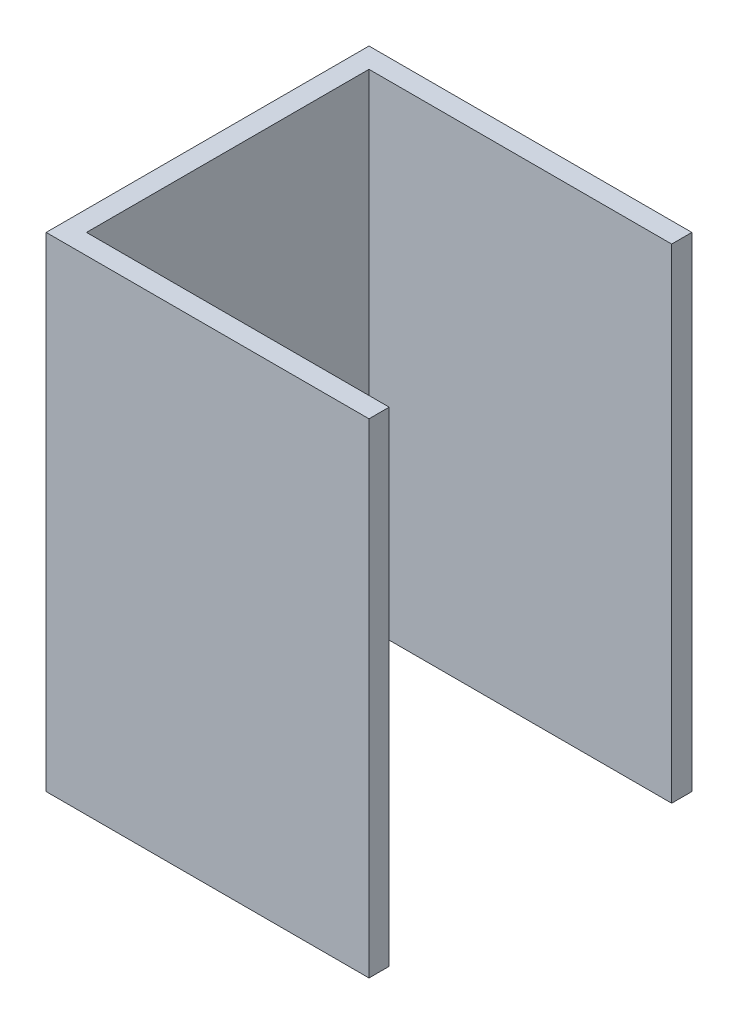
SolidWorks part; units mm, degrees
ref_plane "Front Plane" through (0, 0, 0) normal (0, 0, 1) x (1, 0, 0)
ref_plane "Top Plane" through (0, 0, 0) normal (0, 1, 0) x (1, 0, 0)
ref_plane "Right Plane" through (0, 0, 0) normal (1, 0, 0) x (0, 0, -1)
sketch "Sketch1" plane through (0, 0, 0) normal (0, 1, 0) x (1, 0, 0)
  line L0 (0, 0) -> (-25.4, 0)
  line L1 (-25.4, 0) -> (-25.4, -25.4)
  line L2 (-25.4, -25.4) -> (0, -25.4)
  line L3 (0, -25.4) -> (0, -23.8125)
  line L4 (0, -23.8125) -> (-23.8125, -23.8125)
  line L5 (-23.8125, -23.8125) -> (-23.8125, -1.5875)
  line L6 (-23.8125, -1.5875) -> (0, -1.5875)
  line L7 (0, -1.5875) -> (0, 0)
  dimension "D1" = 25.4
  dimension "D2" = 25.4
  dimension "D3" = 1.5875
  dimension "D4" = 1.5875
  dimension "D5" = 1.5875
extrude "Boss-Extrude1" add sketch "Sketch1" along normal blind 38.1
equation "\"b\"=0.125"
equation "\"t\"=0.0625"
equation "\"D4@Sketch1\"=\"t\""
equation "\"D3@Sketch1\"=\"t\""
equation "\"D5@Sketch1\"=\"t\""
